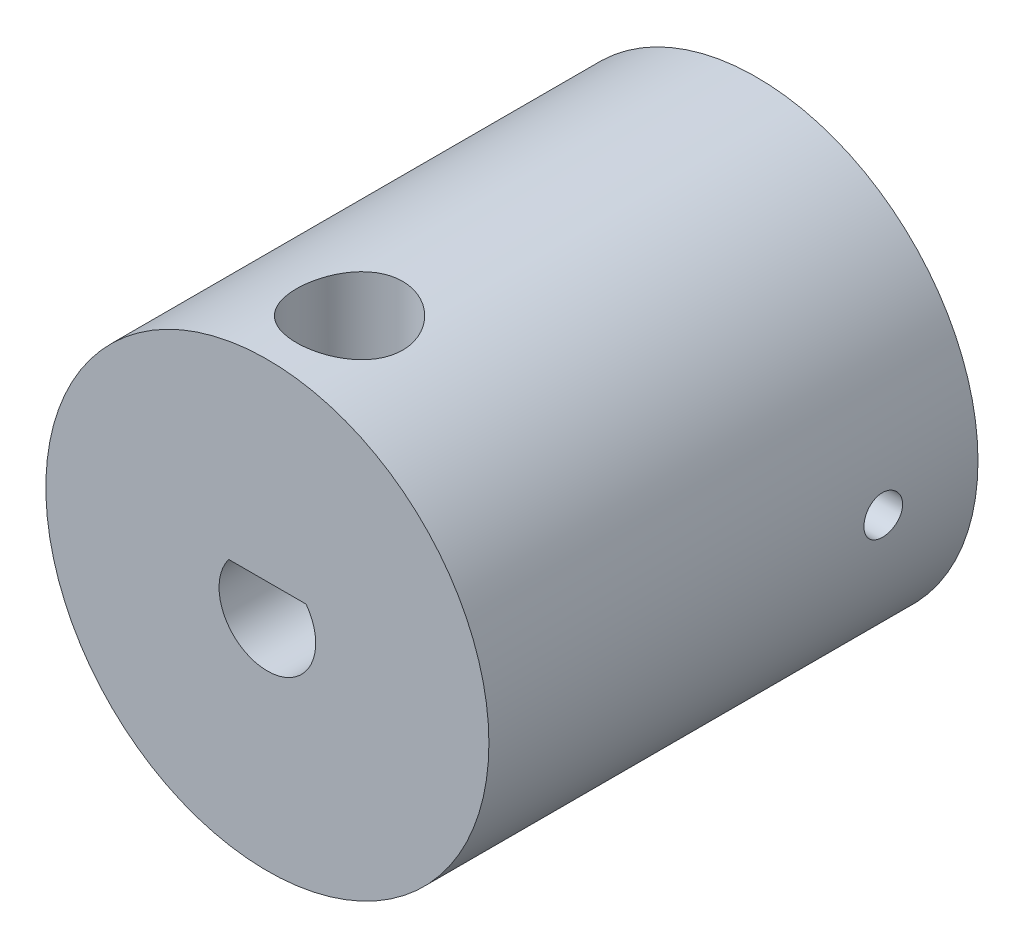
SolidWorks part; units mm, degrees
ref_plane "Front Plane" through (0, 0, 0) normal (0, 0, 1) x (1, 0, 0)
ref_plane "Top Plane" through (0, 0, 0) normal (0, 1, 0) x (1, 0, 0)
ref_plane "Right Plane" through (0, 0, 0) normal (1, 0, 0) x (0, 0, -1)
sketch "Sketch1" plane through (0, 0, 0) normal (0, 0, 1) x (1, 0, 0)
  line L0 (-11.46, 0) -> (11.46, 0) construction
  line L1 (11.46, 0) -> (17.06, 0) construction
  line L2 (-6.75, -6.75) -> (6.75, -6.75)
  line L3 (-6.75, -6.75) -> (-6.75, 6.75)
  line L4 (-6.75, 6.75) -> (6.75, 6.75)
  line L5 (6.75, -6.75) -> (6.75, 6.75)
  line L6 (-6.75, -6.75) -> (6.75, 6.75) construction
  line L7 (-6.75, 6.75) -> (6.75, -6.75) construction
  line L9 (10.7167, 4.06) -> (17.06, 4.06)
  line L11 (10.7167, -4.06) -> (17.06, -4.06)
  line L12 (17.06, 4.06) -> (17.06, -4.06)
  arc A0 (10.7167, 4.06) -> (10.7167, -4.06) centre (0, 0) ccw
  arc A1 (-6.75, 5.1495) -> (-6.75, -5.1495) centre (0, 0) ccw
  arc A2 (-5.1495, -6.75) -> (5.1495, -6.75) centre (0, 0) ccw
  arc A3 (5.1495, 6.75) -> (-5.1495, 6.75) centre (0, 0) ccw
  arc A4 (6.75, -5.1495) -> (6.75, 5.1495) centre (0, 0) ccw
  point P15 (17.06, 0)
  dimension "D1" = 22.92
  dimension "D2" = 2.97
  dimension "D3" = 13.5
  dimension "D4" = 5.6
  dimension "D5" = 8.12
  dimension "D6" = 6.3433
extrude "Boss-Extrude1" add sketch "Sketch1" along normal blind 9.8 contours L9 A0 L11 L12 A4 L5 L2 A2 L3 A1 L4 A3 | L4 A3 | L3 A1 | L5 A4 | L2 A2
sketch "Sketch2" plane through (0, 0, 9.8) normal (0, 0, 1) x (1, 0, 0)
  circle A0 centre (0, 0) radius 9.925
  dimension "D1" = 19.85
extrude "Boss-Extrude2" add sketch "Sketch2" along normal blind 7
sketch "Sketch3" plane through (0, 0, 9.8) normal (0, 0, -1) x (-1, 0, 0)
  line L0 (6.75, 6.75) -> (-6.75, 6.75) construction
  line L1 (-6.75, -6.75) -> (6.75, -6.75)
  line L2 (-6.75, -6.75) -> (-6.75, 6.75)
  line L3 (-6.75, 6.75) -> (6.75, 6.75)
  line L4 (6.75, -6.75) -> (6.75, 6.75)
  line L5 (-6.75, -6.75) -> (6.75, 6.75) construction
  line L6 (-6.75, 6.75) -> (6.75, -6.75) construction
  line L7 (6.75, -6.75) -> (6.75, 6.75) construction
  point P0 (0, 0)
extrude "Cut-Extrude1" cut sketch "Sketch3" against normal blind 5
sketch "Sketch4" plane through (0, 0, 16.8) normal (0, 0, 1) x (1, 0, 0)
  line L0 (0, 2.5) -> (0, 1.5) construction
  line L1 (2, 1.5) -> (-2, 1.5)
  circle A0 centre (0, 0) radius 5
  arc A1 (-2, 1.5) -> (2, 1.5) centre (0, 0) ccw
  dimension "D1" = 10
  dimension "D2" = 5
  dimension "D3" = 1
  dimension "D4" = 4
extrude "Boss-Extrude3" add sketch "Sketch4" along normal blind 8.5
sketch "Sketch5" plane through (17.06, 0, 0) normal (1, 0, 0) x (0, 0, -1)
  line L0 (0, 0) -> (-9.8, 0) construction
  line L1 (-9.8, 4.06) -> (-9.8, -4.06) construction
  circle A0 centre (-4.9, 0) radius 1
  dimension "D1" = 2
extrude "Cut-Extrude2" cut sketch "Sketch5" against normal blind 10.5
sketch "Sketch7" plane through (0, 0, 0) normal (0, 0, -1) x (-1, 0, 0)
  line L1 (-17.06, 4.06) -> (-17.06, -4.06) construction
  line L2 (-17.06, 0) -> (-6.75, 0) construction
  line L3 (-6.75, 6.75) -> (-6.75, -6.75) construction
  line L4 (-10.7167, -4.06) -> (-17.06, -4.06) construction
  line L5 (-17.06, 4.06) -> (-13.56, 4.06)
  line L6 (-17.06, 4.06) -> (-17.06, -4.06)
  line L7 (-17.06, -4.06) -> (-13.56, -4.06)
  line L8 (-13.56, 4.06) -> (-13.56, -4.06)
  dimension "D1" = 3.5
extrude "Cut-Extrude4" cut sketch "Sketch7" against normal blind 10.5
sketch "Sketch9" plane through (0, 0, 16.8) normal (0, 0, 1) x (1, 0, 0)
  circle A1 centre (0, 0) radius 9.925
  circle A2 centre (0, 0) radius 5
extrude "Boss-Extrude4" add sketch "Sketch9" along normal up to surface (8.5 mm away) up to face at (5, 0, 25.3)
sketch "Sketch14" plane through (0, 0, 9.8) normal (0, 0, 1) x (1, 0, 0)
  circle A0 centre (0, 0) radius 9.925
  circle A1 centre (0, 0) radius 11.46
extrude "Boss-Extrude5" add sketch "Sketch14" along normal up to surface (15.5 mm away) up to face at (0, -0.5, 25.3)
sketch "Sketch6" plane through (0, 1.5, 0) normal (0, -1, 0) x (1, 0, 0)
  line L0 (0, 25.3) -> (0, 16.8) construction
  line L1 (5, 25.3) -> (-5, 25.3) construction
  line L2 (9.925, 16.8) -> (-9.925, 16.8) construction
  circle A0 centre (0, 21.05) radius 2.75
  dimension "D1" = 5.5
extrude "Cut-Extrude3" cut sketch "Sketch6" against normal blind 13.5
sketch "Sketch15" plane through (0, 0, 0) normal (0, 0, -1) x (-1, 0, 0)
  line L0 (-10.7167, 4.06) -> (-13.56, 4.06)
  line L1 (-13.56, 4.06) -> (-13.56, -4.06)
  line L2 (-13.56, -4.06) -> (-10.7167, -4.06)
  line L3 (-10.7167, -4.06) -> (-13.56, -4.06) construction
  circle A0 centre (0, 0) radius 11.46
  arc A1 (-10.7167, 4.06) -> (-10.7167, -4.06) centre (0, 0) ccw
  arc A2 (-10.7167, 4.06) -> (-10.7167, -4.06) centre (0, 0) ccw
  line M6 (-10.7167, 4.06) -> (-13.56, 4.06)
  line M7 (-13.56, 4.06) -> (-13.56, -4.06)
  line M8 (-13.56, -4.06) -> (-10.7167, -4.06)
extrude "Cut-Extrude5" cut sketch "Sketch15" against normal blind 21 contours A0 M6 M7 M8
